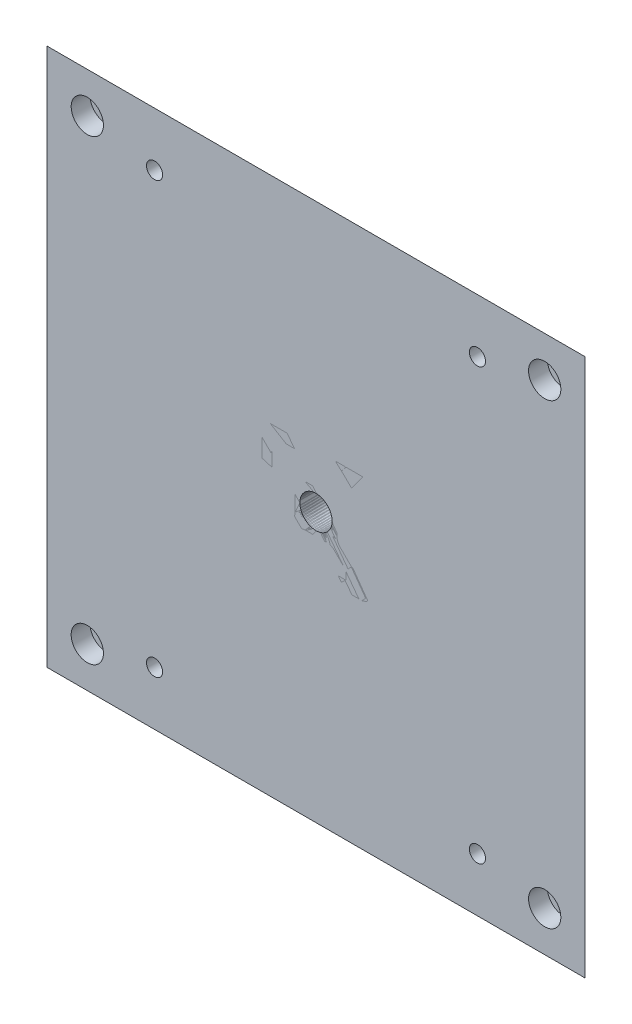
SolidWorks part; units mm, degrees
ref_plane "Спереди" through (0, 0, 0) normal (0, 0, 1) x (1, 0, 0)
ref_plane "Сверху" through (0, 0, 0) normal (0, 1, 0) x (1, 0, 0)
ref_plane "Справа" through (0, 0, 0) normal (1, 0, 0) x (0, 0, -1)
sketch "Sketch1" plane through (0, 0, 0) normal (0, 0, 1) x (1, 0, 0)
  line L0 (0, 10) -> (0, -10) construction
  line L1 (-10, -10) -> (10, -10) construction
  line L2 (-10, -10) -> (-10, 10) construction
  line L3 (-10, 10) -> (10, 10) construction
  line L4 (10, -10) -> (10, 10) construction
  line L5 (-10, -10) -> (10, 10) construction
  line L6 (-10, 10) -> (10, -10) construction
  line L7 (-10, 0) -> (10, 0) construction
  line L8 (0, 3.9) -> (-2.0109, 3.9)
  line L9 (-3.4251, 4.4858) -> (-5.5393, 6.6)
  line L10 (-5.5393, 6.6) -> (-5.5393, 8.2)
  line L11 (-5.5393, 8.2) -> (-3.1, 8.2)
  line L12 (-3.1, 8.2) -> (-3.1, 9.5)
  line L13 (-3.1, 9.5) -> (-3.4, 9.5)
  line L14 (-3.6, 9.7) -> (-3.6, 10)
  line L15 (-3.6, 10) -> (-8.5, 10)
  line L16 (-10, 3.6) -> (-10, 8.5)
  line L17 (-9.7, 3.6) -> (-10, 3.6)
  line L18 (-9.5, 3.1) -> (-9.5, 3.4)
  line L19 (-8.2, 3.1) -> (-9.5, 3.1)
  line L20 (-8.2, 5.5393) -> (-8.2, 3.1)
  line L21 (-6.6, 5.5393) -> (-8.2, 5.5393)
  line L22 (-4.4858, 3.4251) -> (-6.6, 5.5393)
  line L23 (-3.9, 0) -> (-3.9, 2.0109)
  line L24 (3.9, 0) -> (3.9, 2.0109)
  line L25 (4.4858, 3.4251) -> (6.6, 5.5393)
  line L26 (6.6, 5.5393) -> (8.2, 5.5393)
  line L27 (8.2, 5.5393) -> (8.2, 3.1)
  line L28 (8.2, 3.1) -> (9.5, 3.1)
  line L29 (9.5, 3.1) -> (9.5, 3.4)
  line L30 (9.7, 3.6) -> (10, 3.6)
  line L31 (10, 3.6) -> (10, 8.5)
  line L32 (3.6, 10) -> (8.5, 10)
  line L33 (3.6, 9.7) -> (3.6, 10)
  line L34 (3.1, 9.5) -> (3.4, 9.5)
  line L35 (3.1, 8.2) -> (3.1, 9.5)
  line L36 (5.5393, 8.2) -> (3.1, 8.2)
  line L37 (5.5393, 6.6) -> (5.5393, 8.2)
  line L38 (3.4251, 4.4858) -> (5.5393, 6.6)
  line L39 (0, 3.9) -> (2.0109, 3.9)
  line L40 (0, -3.9) -> (2.0109, -3.9)
  line L41 (3.4251, -4.4858) -> (5.5393, -6.6)
  line L42 (5.5393, -6.6) -> (5.5393, -8.2)
  line L43 (5.5393, -8.2) -> (3.1, -8.2)
  line L44 (3.1, -8.2) -> (3.1, -9.5)
  line L45 (3.1, -9.5) -> (3.4, -9.5)
  line L46 (3.6, -9.7) -> (3.6, -10)
  line L47 (3.6, -10) -> (8.5, -10)
  line L48 (10, -3.6) -> (10, -8.5)
  line L49 (9.7, -3.6) -> (10, -3.6)
  line L50 (9.5, -3.1) -> (9.5, -3.4)
  line L51 (8.2, -3.1) -> (9.5, -3.1)
  line L52 (8.2, -5.5393) -> (8.2, -3.1)
  line L53 (6.6, -5.5393) -> (8.2, -5.5393)
  line L54 (4.4858, -3.4251) -> (6.6, -5.5393)
  line L55 (3.9, 0) -> (3.9, -2.0109)
  line L56 (-3.9, 0) -> (-3.9, -2.0109)
  line L57 (-4.4858, -3.4251) -> (-6.6, -5.5393)
  line L58 (-6.6, -5.5393) -> (-8.2, -5.5393)
  line L59 (-8.2, -5.5393) -> (-8.2, -3.1)
  line L60 (-8.2, -3.1) -> (-9.5, -3.1)
  line L61 (-9.5, -3.1) -> (-9.5, -3.4)
  line L62 (-9.7, -3.6) -> (-10, -3.6)
  line L63 (-10, -3.6) -> (-10, -8.5)
  line L64 (-3.6, -10) -> (-8.5, -10)
  line L65 (-3.6, -9.7) -> (-3.6, -10)
  line L66 (-3.1, -9.5) -> (-3.4, -9.5)
  line L67 (-3.1, -8.2) -> (-3.1, -9.5)
  line L68 (-5.5393, -8.2) -> (-3.1, -8.2)
  line L69 (-5.5393, -6.6) -> (-5.5393, -8.2)
  line L70 (-3.4251, -4.4858) -> (-5.5393, -6.6)
  line L71 (0, -3.9) -> (-2.0109, -3.9)
  circle A0 centre (0, 0) radius 3
  arc A1 (-8.5, 10) -> (-10, 8.5) centre (-8.5, 8.5) ccw
  arc A2 (-2.0109, 3.9) -> (-3.4251, 4.4858) centre (-2.0109, 5.9) cw
  arc A3 (-3.4, 9.5) -> (-3.6, 9.7) centre (-3.4, 9.7) cw
  arc A4 (-9.5, 3.4) -> (-9.7, 3.6) centre (-9.7, 3.4) ccw
  arc A5 (-3.9, 2.0109) -> (-4.4858, 3.4251) centre (-5.9, 2.0109) ccw
  arc A6 (10, 8.5) -> (8.5, 10) centre (8.5, 8.5) ccw
  arc A7 (3.9, 2.0109) -> (4.4858, 3.4251) centre (5.9, 2.0109) cw
  arc A8 (9.5, 3.4) -> (9.7, 3.6) centre (9.7, 3.4) cw
  arc A9 (3.4, 9.5) -> (3.6, 9.7) centre (3.4, 9.7) ccw
  arc A10 (2.0109, 3.9) -> (3.4251, 4.4858) centre (2.0109, 5.9) ccw
  arc A11 (8.5, -10) -> (10, -8.5) centre (8.5, -8.5) ccw
  arc A12 (2.0109, -3.9) -> (3.4251, -4.4858) centre (2.0109, -5.9) cw
  arc A13 (3.4, -9.5) -> (3.6, -9.7) centre (3.4, -9.7) cw
  arc A14 (9.5, -3.4) -> (9.7, -3.6) centre (9.7, -3.4) ccw
  arc A15 (3.9, -2.0109) -> (4.4858, -3.4251) centre (5.9, -2.0109) ccw
  arc A16 (-10, -8.5) -> (-8.5, -10) centre (-8.5, -8.5) ccw
  arc A17 (-3.9, -2.0109) -> (-4.4858, -3.4251) centre (-5.9, -2.0109) cw
  arc A18 (-9.5, -3.4) -> (-9.7, -3.6) centre (-9.7, -3.4) cw
  arc A19 (-3.4, -9.5) -> (-3.6, -9.7) centre (-3.4, -9.7) ccw
  arc A20 (-2.0109, -3.9) -> (-3.4251, -4.4858) centre (-2.0109, -5.9) ccw
  point P0 (0, 0)
  point P42 (0, 0)
  point P70 (0, 0)
  point P98 (0, 0)
  point P126 (0, 0)
  dimension "D3" = 6
  dimension "D4" = 3
  dimension "D12" = 2
  dimension "D13" = 0.2
  dimension "D1" = 20
  dimension "D2" = 20
  dimension "D5" = 6.2
  dimension "D6" = 7.2
  dimension "D7" = 1.8
  dimension "D8" = 0.5
  dimension "D9" = 3.4
  dimension "D10" = 1.5
  dimension "D11" = 6.1
  dimension "D14" = 4
extrude "Бобышка-Вытянуть1" add sketch "Sketch1" along normal blind 175
sketch "Эскиз1" plane through (0, 0, 175) normal (0, 0, 1) x (1, 0, 0)
  line L0 (0, 50) -> (0, -50) construction
  line L1 (-50, -50) -> (50, -50)
  line L2 (-50, -50) -> (-50, 50)
  line L3 (-50, 50) -> (50, 50)
  line L4 (50, -50) -> (50, 50)
  line L6 (50, 0) -> (-50, 0) construction
  point P6 (0, 0)
  dimension "D1" = 0
  dimension "D2" = 100
  dimension "D3" = 100
extrude "Бобышка-Вытянуть2" add sketch "Эскиз1" against normal blind 40 draft 45 separate body
sketch "Эскиз3" plane through (0, 0, 175) normal (0, 0, 1) x (1, 0, 0)
  line L0 (0, 0) -> (0, 10.5282) construction
  line L1 (0, 0) -> (-15.3247, 0) construction
  line L2 (-30, 41.5) -> (-27.7821, 41.5) construction
  line L3 (-31.5, 40) -> (-31.5, 30.3399) construction
  circle A0 centre (-30, 40) radius 1.5
  circle A1 centre (30, 40) radius 1.5
  circle A2 centre (30, -40) radius 1.5
  circle A3 centre (-30, -40) radius 1.5
  dimension "D1" = 60
  dimension "D3" = 3
  dimension "D2" = 80
extrude "Вырез-Вытянуть2" cut sketch "Эскиз3" against normal blind 40
sketch "Эскиз4" plane through (0, 62.5, 62.5) normal (0, -0.7071, -0.7071) x (1, 0, 0)
  line L0 (-30, 143.8962) -> (-30, 152.028) construction
  line L1 (-34, 140.9569) -> (-26, 140.9569)
  line L2 (-34, 140.9569) -> (-34, 148.9569)
  line L3 (-34, 148.9569) -> (-26, 148.9569)
  line L4 (-26, 140.9569) -> (-26, 148.9569)
  line L5 (-34, 140.9569) -> (-26, 148.9569) construction
  line L6 (-34, 148.9569) -> (-26, 140.9569) construction
  line L11 (34, 140.9569) -> (34, 148.9569)
  line L12 (34, 140.9569) -> (26, 140.9569)
  line L13 (0, 159.099) -> (0, 102.5305) construction
  line L14 (-50, 159.099) -> (50, 159.099) construction
  line L15 (-10, 102.5305) -> (10, 102.5305) construction
  line L16 (26, 140.9569) -> (26, 148.9569)
  line L17 (34, 148.9569) -> (26, 148.9569)
  point P0 (-30, 144.9569)
  dimension "D1" = 8
  dimension "D2" = 8
  dimension "D3" = 0
  dimension "D4" = 0
  dimension "D5" = 30
revolve "Вырез-Повернуть1" cut sketch "Эскиз4" angle 45 about L3
sketch "Эскиз6" plane through (0, 0, 0) normal (0, 0, -1) x (-1, 0, 0)
  circle A0 centre (0, 0) radius 3
  dimension "D1" = 6
extrude "Вырез-Вытянуть4" cut sketch "Эскиз6" against normal up to surface (175 mm away) and the other way through all up to face at (-31.5, -40, 175)
sketch "Эскиз8" plane through (0, 0, 175) normal (0, 0, 1) x (1, 0, 0)
  line L0 (0, 50) -> (0, -50) construction
  line L1 (50, 50) -> (-50, 50) construction
  line L2 (-50, -50) -> (50, -50) construction
  line L3 (-42.5, 45.5) -> (42.5, 45.5) construction
  line L4 (-50, 50) -> (-50, -50) construction
  line L5 (-50, 0) -> (50, 0) construction
  line L6 (50, -50) -> (50, 50) construction
  line L7 (-45.5, 42.5) -> (-45.5, -42.5) construction
  circle A0 centre (-42.5, 42.5) radius 3
  circle A1 centre (42.5, 42.5) radius 3
  circle A2 centre (42.5, -42.5) radius 3
  circle A3 centre (-42.5, -42.5) radius 3
  dimension "D1" = 6
  dimension "D2" = 45.5
  dimension "D3" = 45.5
extrude "Вырез-Вытянуть6" cut sketch "Эскиз8" against normal blind 3.5
sketch "Эскиз9" plane through (0, 0, 0) normal (0, 0, -1) x (-1, 0, 0)
  line L0 (10, 10) -> (50, 50) construction
  line L5 (-10.15, -10.15) -> (10.15, -10.15)
  line L6 (-10.15, -10.15) -> (-10.15, 10.15)
  line L7 (-10.15, 10.15) -> (10.15, 10.15)
  line L8 (10.15, -10.15) -> (10.15, 10.15)
  line L9 (-10.15, -10.15) -> (10.15, 10.15) construction
  line L10 (-10.15, 10.15) -> (10.15, -10.15) construction
  point P0 (0, 0)
  dimension "D1" = 20.3
extrude "Вырез-Вытянуть7" cut sketch "Эскиз9" against normal offset from surface (169 mm away) 6 up to face at (-45.5, -42.5, 175)
sketch "Эскиз10" plane through (0, -62.5, 62.5) normal (0, 0.7071, -0.7071) x (1, 0, 0)
  line L0 (-31.5, -144.9569) -> (-28.5, -144.9569) construction
  line L1 (-30, -142.8356) -> (-30, -147.0782) construction
  line L2 (0, -102.7426) -> (0, -159.099) construction
  line L3 (-34, -148.9569) -> (-26, -148.9569)
  line L4 (-34, -148.9569) -> (-34, -140.9569)
  line L5 (-34, -140.9569) -> (-26, -140.9569)
  line L6 (-26, -148.9569) -> (-26, -140.9569)
  line L7 (-34, -148.9569) -> (-26, -140.9569) construction
  line L8 (-34, -140.9569) -> (-26, -148.9569) construction
  line L9 (-10.15, -102.7426) -> (10.15, -102.7426) construction
  line L10 (50, -159.099) -> (-50, -159.099) construction
  line L11 (34, -140.9569) -> (26, -148.9569) construction
  line L12 (34, -148.9569) -> (26, -140.9569) construction
  line L13 (30, -142.8356) -> (30, -147.0782) construction
  line L14 (31.5, -144.9569) -> (28.5, -144.9569) construction
  line L15 (26, -148.9569) -> (26, -140.9569)
  line L16 (34, -140.9569) -> (26, -140.9569)
  line L17 (34, -148.9569) -> (34, -140.9569)
  line L18 (34, -148.9569) -> (26, -148.9569)
  ellipse E0 centre (-30, -144.9569) end of major axis (-30, -147.0782) minor radius 1.5 construction
  point P12 (-30, -144.9569)
  point P31 (30, -144.9569)
  dimension "D1" = 8
  dimension "D2" = 8
revolve "Вырез-Повернуть3" cut sketch "Эскиз10" angle 45 about L18
